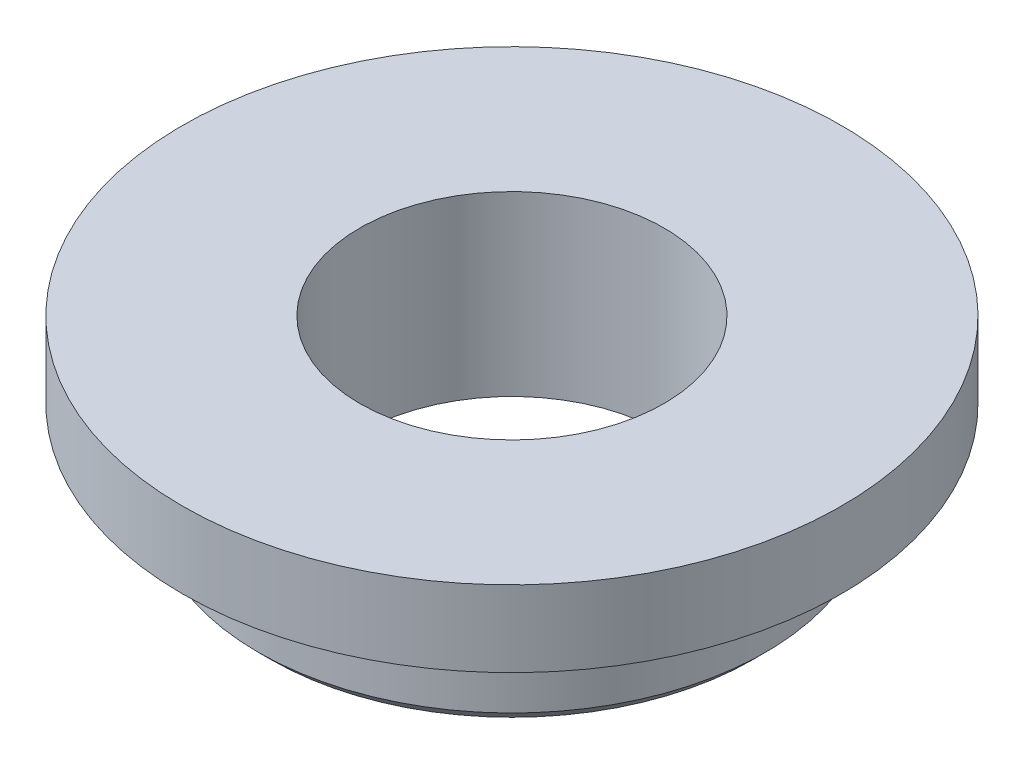
SolidWorks part; units mm, degrees
ref_plane "Front Plane" through (0, 0, 0) normal (0, 0, 1) x (1, 0, 0)
ref_plane "Top Plane" through (0, 0, 0) normal (0, 1, 0) x (1, 0, 0)
ref_plane "Right Plane" through (0, 0, 0) normal (1, 0, 0) x (0, 0, -1)
sketch "Sketch1" plane through (0, 0, 0) normal (0, 1, 0) x (1, 0, 0)
  circle A0 centre (0, 0) radius 13
  dimension "D1" = 26
extrude "Boss-Extrude1" add sketch "Sketch1" along normal blind 3
sketch "Sketch2" plane through (0, 0, 0) normal (0, -1, 0) x (1, 0, 0)
  circle A0 centre (0, 0) radius 10
  dimension "D1" = 20
extrude "Boss-Extrude2" add sketch "Sketch2" along normal blind 4
chamfer "Chamfer1" distance 0.5 angle 45 2 edges at (0, 0, -10) (0, -4, -10)
sketch "Sketch3" plane through (0, 3, 0) normal (0, 1, 0) x (1, 0, 0)
  circle A0 centre (0, 0) radius 6
  dimension "D1" = 12
extrude "Cut-Extrude1" cut sketch "Sketch3" against normal through all
